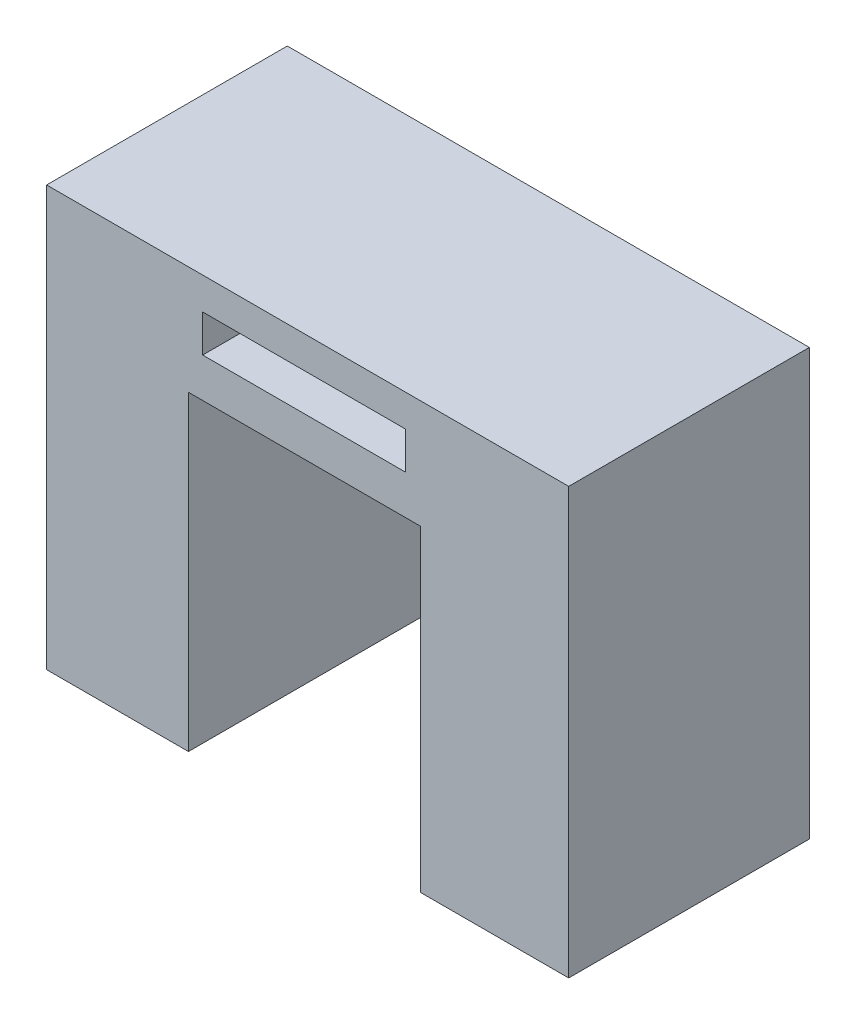
SolidWorks part; units mm, degrees
ref_plane "Front Plane" through (0, 0, 0) normal (0, 0, 1) x (1, 0, 0)
ref_plane "Top Plane" through (0, 0, 0) normal (0, 1, 0) x (1, 0, 0)
ref_plane "Right Plane" through (0, 0, 0) normal (1, 0, 0) x (0, 0, -1)
sketch "Sketch1" plane through (0, 0, 0) normal (0, 0, 1) x (1, 0, 0)
  line L1 (0, 92.7931) -> (80.1034, 92.7931)
  line L2 (0, 92.7931) -> (0, -137.2069)
  line L3 (0, -137.2069) -> (80.1034, -137.2069)
  line L4 (80.1034, 92.7931) -> (80.1034, -137.2069)
  line L5 (-125.3103, 92.7931) -> (0, 92.7931)
  line L7 (-125.3103, 34.1034) -> (0, 34.1034)
  line L9 (-125.3103, 92.7931) -> (-201.9063, 92.7931)
  line L10 (-125.3103, 92.7931) -> (-125.3103, -133.9772)
  line L11 (-125.3103, -133.9772) -> (-201.9063, -133.9772)
  line L12 (-201.9063, 92.7931) -> (-201.9063, -133.9772)
  dimension "D1" = 230
extrude "Boss-Extrude1" add sketch "Sketch1" along normal blind 130 contours L9 L12 L11 L10 | L5 L10 L7 L2 | L4 L1 L2 L3
sketch "Sketch3" plane through (0, 0, 130) normal (0, 0, 1) x (1, 0, 0)
  line L1 (-117.6242, 75.5202) -> (-7.9374, 75.5202)
  line L2 (-117.6242, 75.5202) -> (-117.6242, 55.3597)
  line L3 (-117.6242, 55.3597) -> (-7.9374, 55.3597)
  line L4 (-7.9374, 75.5202) -> (-7.9374, 55.3597)
extrude "Cut-Extrude1" cut sketch "Sketch3" against normal blind 100
sketch "Sketch7" plane through (0, 34.1034, 0) normal (0, -1, 0) x (-1, 0, 0)
  line L0 (117.6242, -39.0412) -> (9.3673, -39.0412) construction
  line L1 (117.6242, -130) -> (117.6242, -39.0412) construction
  line L2 (9.3673, -39.0412) -> (9.3673, -130) construction
  line L3 (125.3103, -130) -> (0, -130) construction
  line L5 (117.6242, -39.0412) -> (9.3673, -39.0412)
  line L6 (117.6242, -39.0412) -> (117.6242, -89.0412)
  line L7 (117.6242, -89.0412) -> (9.3673, -89.0412)
  line L8 (9.3673, -39.0412) -> (9.3673, -89.0412)
  dimension "D1" = 50
extrude "Cut-Extrude3" cut sketch "Sketch7" against normal blind 40
